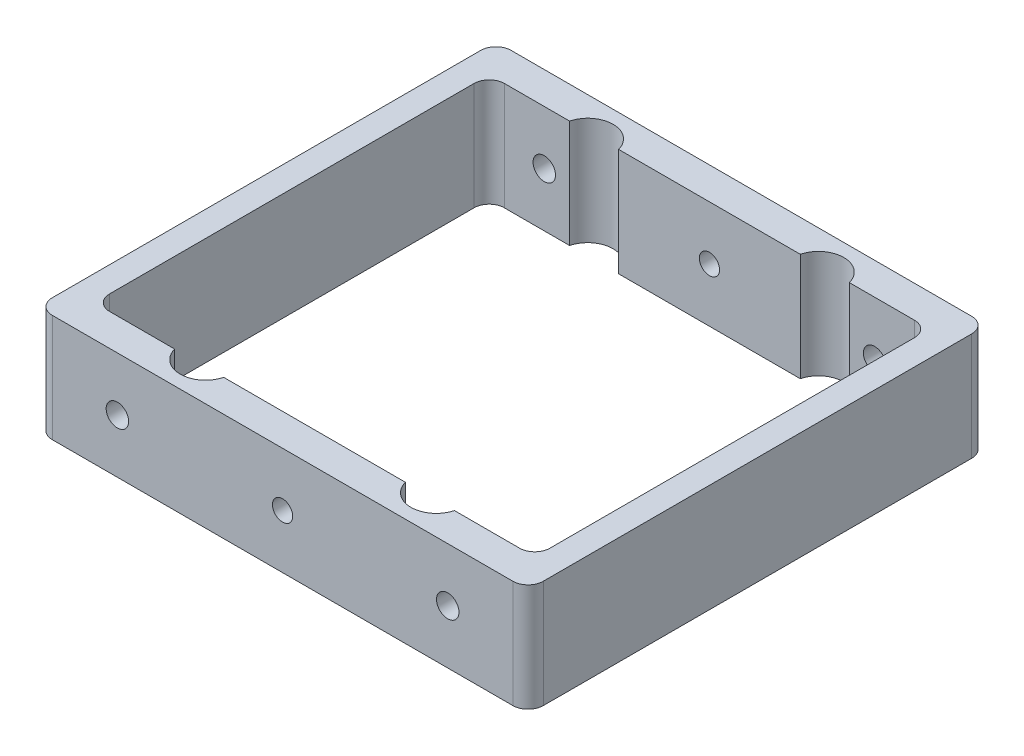
SolidWorks part; units mm, degrees
ref_plane "Front Plane" through (0, 0, 0) normal (0, 0, 1) x (1, 0, 0)
ref_plane "Top Plane" through (0, 0, 0) normal (0, 1, 0) x (1, 0, 0)
ref_plane "Right Plane" through (0, 0, 0) normal (1, 0, 0) x (0, 0, -1)
sketch "Sketch1" plane through (0, 0, 0) normal (0, 1, 0) x (1, 0, 0)
  line L1 (0, 0) -> (60, 0)
  line L2 (0, 0) -> (0, -6.32)
  line L3 (0, -6.32) -> (60, -6.32)
  line L4 (60, 0) -> (60, -6.32)
  dimension "D1" = 60
  dimension "D2" = 6.32
extrude "Boss-Extrude1" add sketch "Sketch1" along normal mid plane 21.28
sketch "Sketch2" plane through (0, 10.64, 0) normal (0, 1, 0) x (1, 0, 0)
  line L0 (0, 0) -> (0, -6.32) construction
  line L1 (0, -6.32) -> (60, -6.32) construction
  line L2 (60, -6.32) -> (60, 0) construction
  circle A0 centre (7.21, 1.25) radius 5
  circle A1 centre (52.79, 1.25) radius 5
  dimension "D1" = 7.21
  dimension "D3" = 7.21
  dimension "D2" = 7.57
  dimension "D4" = 7.57
extrude "Cut-Extrude1" cut sketch "Sketch2" against normal through all
sketch "Sketch3" plane through (60, 0, 0) normal (1, 0, 0) x (0, 0, -1)
  line L1 (-6.32, 10.64) -> (0, 10.64)
  line L2 (-6.32, 10.64) -> (-6.32, -10.64)
  line L3 (-6.32, -10.64) -> (0, -10.64)
  line L4 (0, 10.64) -> (0, -10.64)
extrude "Boss-Extrude2" add sketch "Sketch3" along normal blind 18.5
sketch "Sketch4" plane through (0, 0, 0) normal (-1, 0, 0) x (0, 0, 1)
  line L1 (0, 10.64) -> (6.32, 10.64)
  line L2 (0, 10.64) -> (0, -10.64)
  line L3 (0, -10.64) -> (6.32, -10.64)
  line L4 (6.32, 10.64) -> (6.32, -10.64)
extrude "Boss-Extrude3" add sketch "Sketch4" along normal blind 18.5
sketch "Sketch5" plane through (0, 0, 0) normal (0, 0, -1) x (-1, 0, 0)
  line L5 (-2.3688, -10.64) -> (18.5, -10.64) construction
  line L6 (18.5, 10.64) -> (13.5, 10.64)
  line L7 (18.5, 10.64) -> (18.5, -10.64)
  line L8 (18.5, -10.64) -> (13.5, -10.64)
  line L9 (13.5, 10.64) -> (13.5, -10.64)
  dimension "D1" = 5
extrude "Boss-Extrude6" add sketch "Sketch5" along normal blind 84.33
sketch "Sketch6" plane through (0, 0, 0) normal (0, 0, -1) x (-1, 0, 0)
  line L1 (-78.5, 10.64) -> (-73.5, 10.64)
  line L2 (-78.5, 10.64) -> (-78.5, -10.652)
  line L3 (-78.5, -10.652) -> (-73.5, -10.652)
  line L4 (-73.5, 10.64) -> (-73.5, -10.652)
  dimension "D1" = 5
extrude "Boss-Extrude7" add sketch "Sketch6" along normal blind 84.33
sketch "Sketch7" plane through (73.5, 0, 0) normal (-1, 0, 0) x (0, 0, 1)
  line L0 (-84.33, -10.652) -> (0, -10.652) construction
  line L1 (-84.33, 10.64) -> (-78.01, 10.64)
  line L2 (-84.33, 10.64) -> (-84.33, -10.652)
  line L3 (-84.33, -10.652) -> (-78.01, -10.652)
  line L4 (-78.01, 10.64) -> (-78.01, -10.652)
  dimension "D1" = 6.32
extrude "Boss-Extrude8" add sketch "Sketch7" along normal through all
sketch "Sketch9" plane through (0, 10.64, 0) normal (0, 1, 0) x (1, 0, 0)
  line L0 (-18.5, 84.33) -> (78.5, 84.33) construction
  circle A0 centre (7.21, 76.76) radius 5
  circle A1 centre (52.79, 76.76) radius 5
  dimension "D1" = 7.57
  dimension "D2" = 7.57
  dimension "D3" = 10
extrude "Cut-Extrude2" cut sketch "Sketch9" against normal through all
sketch "Sketch10" plane through (0, 0, -84.33) normal (0, 0, -1) x (-1, 0, 0)
  line L1 (-78.5, -10.64) -> (18.5, -10.64) construction
  line L2 (-30, -10.64) -> (-30, 10.64) construction
  line L3 (18.5, 10.64) -> (-78.5, 10.64) construction
  circle A0 centre (-62.6312, 0.005) radius 2.22
  circle A1 centre (2.6312, 0.005) radius 2.22
  dimension "D1" = 5
  dimension "D2" = 10.645
extrude "Cut-Extrude3" cut sketch "Sketch10" against normal through all
fillet "Fillet1" radius 3 8 edges at (-18.5, 0, 6.32) (78.5, 0, 6.32) (78.5, -0.006, -84.33) (-18.5, -0.006, -84.33) (-13.5, 0, -78.01) (-13.5, 0, 0) (73.5, -0.006, -78.01) (73.5, 0, 0)
sketch "Sketch13" plane through (0, 0, -84.33) normal (0, 0, -1) x (-1, 0, 0)
  line L1 (-75.5, 10.64) -> (-75.5, -10.652) construction
  line L2 (-75.5, -10.64) -> (15.5, -10.64) construction
  circle A0 centre (-30, 0.005) radius 2
  dimension "D1" = 45.5
  dimension "D2" = 10.645
extrude "Cut-Extrude4" cut sketch "Sketch13" against normal through all
